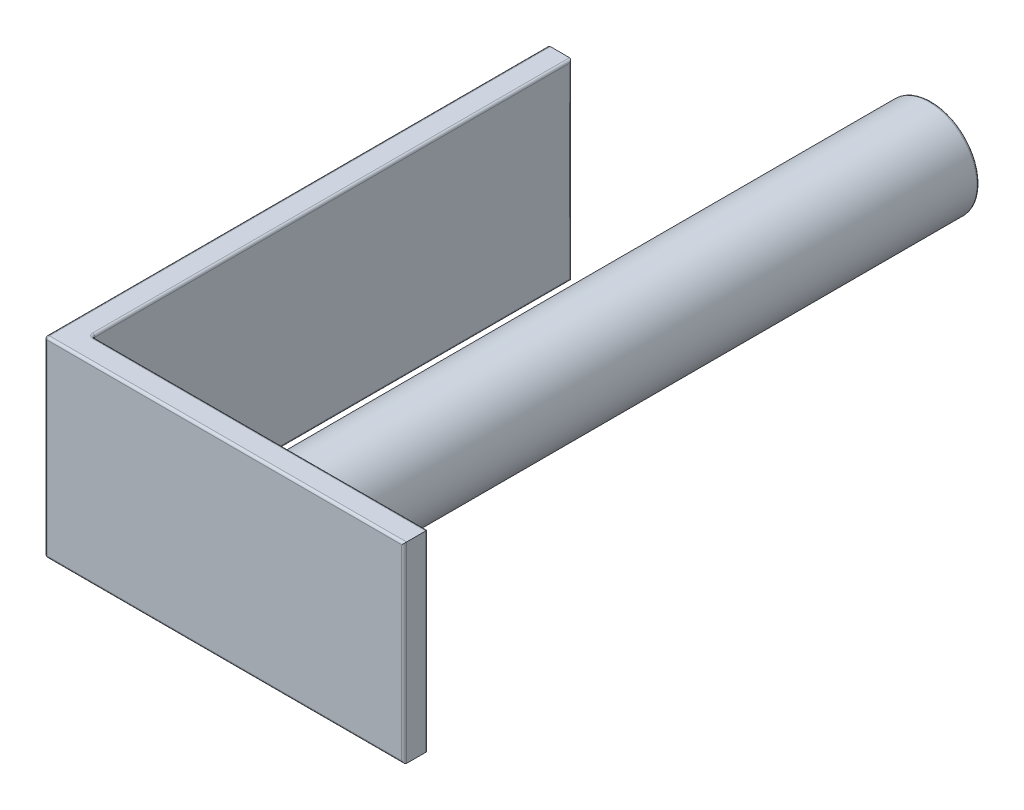
SolidWorks part; units mm, degrees
ref_plane "Front Plane" through (0, 0, 0) normal (0, 0, 1) x (1, 0, 0)
ref_plane "Top Plane" through (0, 0, 0) normal (0, 1, 0) x (1, 0, 0)
ref_plane "Right Plane" through (0, 0, 0) normal (1, 0, 0) x (0, 0, -1)
sketch "Sketch1" plane through (0, 0, 0) normal (0, 0, 1) x (1, 0, 0)
  circle A0 centre (0, 0) radius 50.8
  dimension "D1" = 101.6
extrude "Boss-Extrude1" add sketch "Sketch1" against normal blind 711.2
sketch "Sketch3" plane through (0, 0, 0) normal (0, 1, 0) x (1, 0, 0)
  line L0 (177.8, 0) -> (-177.8, 0)
  line L1 (-177.8, 0) -> (-177.8, 508)
  point P3 (0, 0)
  dimension "D1" = 355.6
  dimension "D2" = 508
extrude "Extrude-Thin1" add sketch "Sketch3" along normal mid plane 203.2 thin thin type one direction reverse wall 25.4
fillet "Fillet1" radius 2.54 16 edges at (0, -101.6, 0) (-203.2, 0, 25.4) (-12.7, 101.6, 25.4) (177.8, 0, 25.4) (-12.7, -101.6, 25.4) (50.8, 0, 0) (50.8, 0, -711.2) (-177.8, 0, 0) (-203.2, 0, -508) (-177.8, 0, -508) (177.8, 0, 0) (-177.8, -101.6, -254) (-203.2, 101.6, -241.3) (-203.2, -101.6, -241.3) (-177.8, 101.6, -254) (0, 101.6, 0)
